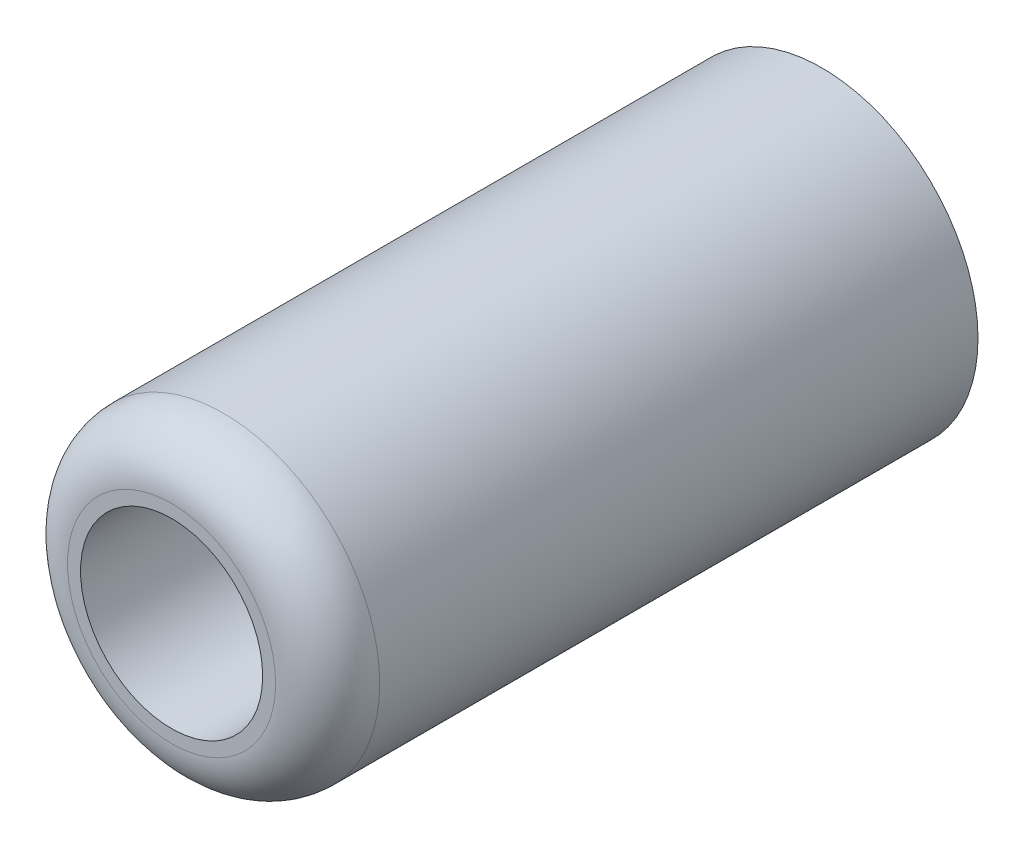
SolidWorks part; units mm, degrees
ref_plane "正面" through (0, 0, 0) normal (0, 0, 1) x (1, 0, 0)
ref_plane "平面" through (0, 0, 0) normal (0, 1, 0) x (1, 0, 0)
ref_plane "右側面" through (0, 0, 0) normal (1, 0, 0) x (0, 0, -1)
sketch "ｽｹｯﾁ1" plane through (0, 0, 0) normal (0, 0, 1) x (1, 0, 0)
  circle A0 centre (0, 0) radius 1.75
  circle A1 centre (0, 0) radius 3
  dimension "D1" = 6
  dimension "D2" = 3.5
extrude "ﾎﾞｽ - 押し出し1" add sketch "ｽｹｯﾁ1" along normal blind 12.5
fillet "ﾌｨﾚｯﾄ2" radius 1 1 edges at (3, 0, 12.5)
